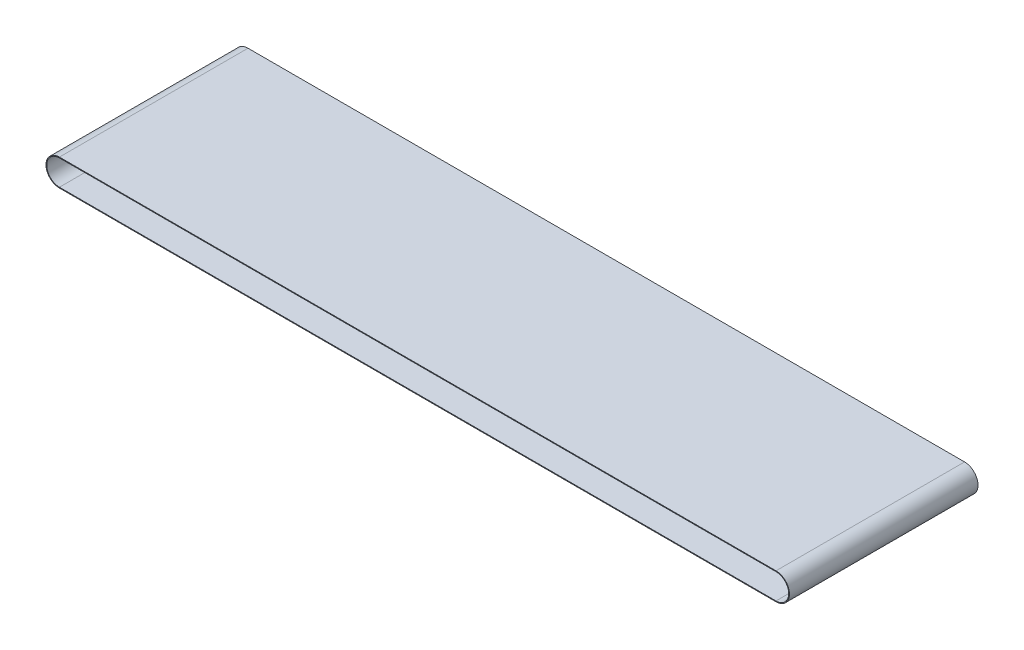
SolidWorks part; units mm, degrees
ref_plane "Front Plane" through (0, 0, 0) normal (0, 0, 1) x (1, 0, 0)
ref_plane "Top Plane" through (0, 0, 0) normal (0, 1, 0) x (1, 0, 0)
ref_plane "Right Plane" through (0, 0, 0) normal (1, 0, 0) x (0, 0, -1)
sketch "Sketch2" plane through (0, 0, 0) normal (0, 0, 1) x (1, 0, 0)
  line L0 (0, 0) -> (1, 0) construction
  line L1 (0, 0) -> (0, 1) construction
  line L2 (0, 16.8) -> (950, 16.8)
  line L3 (950, -16.8) -> (0, -16.8)
  arc A0 (0, -16.8) -> (0, 16.8) centre (0, 0) cw
  arc A1 (950, 16.8) -> (950, -16.8) centre (950, 0) cw
extrude "Extrude-Thin1" add sketch "Sketch2" against normal blind 250 from offset 5 thin thin type one direction wall 1 offset against normal yes
